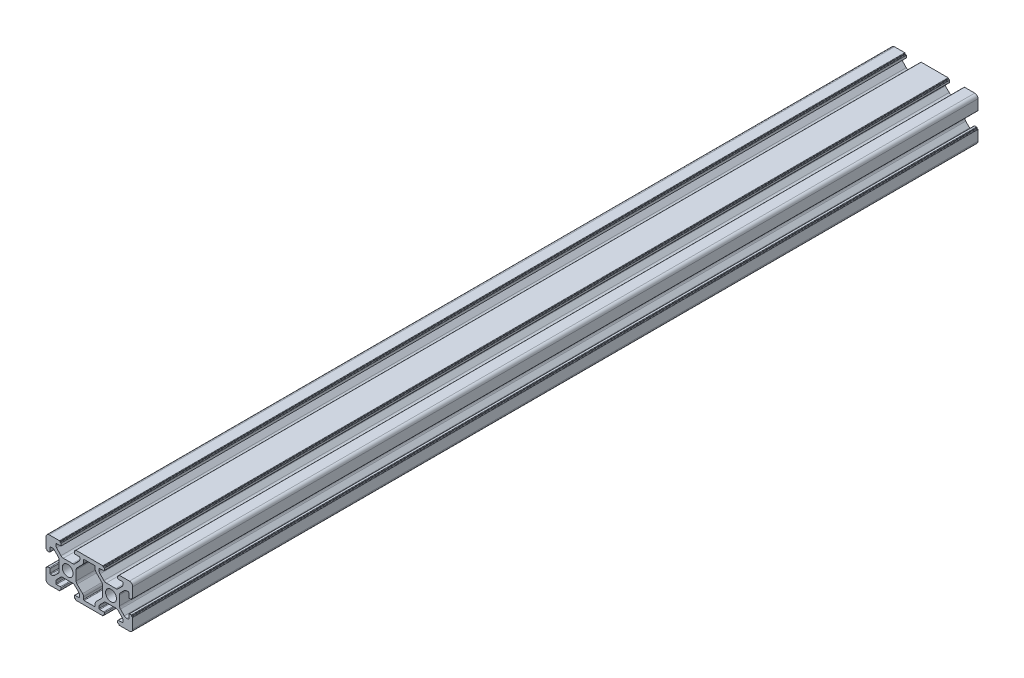
SolidWorks part; units mm, degrees
material "6063-T5"
ref_plane "Front Plane" through (0, 0, 0) normal (0, 0, 1) x (1, 0, 0)
ref_plane "Top Plane" through (0, 0, 0) normal (0, 1, 0) x (1, 0, 0)
ref_plane "Right Plane" through (0, 0, 0) normal (1, 0, 0) x (0, 0, -1)
sketch "Sketch1" plane through (0, 0, 0) normal (0, 0, 1) x (1, 0, 0)
  line L0 (1.5, 0) -> (6.2, 0)
  line L1 (40, 1.5) -> (40, 6.2)
  line L2 (38.5, 20) -> (33.8, 20)
  line L3 (0, 18.5) -> (0, 13.8)
  line L4 (17.6, 1.8) -> (22.4, 1.8)
  line L5 (32.218, 13.9) -> (27.782, 13.9)
  line L6 (26.1, 12.218) -> (26.1, 7.782)
  line L7 (17.6, 18.2) -> (22.4, 18.2)
  line L8 (12.218, 13.9) -> (7.9864, 13.9)
  line L9 (6.1, 12.218) -> (6.1, 7.782)
  line L10 (7.782, 6.1) -> (12.218, 6.1)
  line L11 (13.9, 7.782) -> (13.9, 12.218)
  line L12 (27.782, 6.1) -> (32.218, 6.1)
  line L13 (33.9, 7.782) -> (33.9, 12.218)
  line L14 (26.7213, 14.3393) -> (24.9393, 16.1213)
  line L15 (33.2787, 14.3393) -> (35.0607, 16.1213)
  line L16 (34.3393, 13.2787) -> (36.1213, 15.0607)
  line L17 (25.6607, 6.7213) -> (23.1393, 4.2)
  line L18 (15.2, 1.8) -> (13.4, 1.8)
  line L19 (26.7213, 5.6607) -> (24.9393, 3.8787)
  line L20 (24.8, 1.8) -> (26.6, 1.8)
  line L21 (15.3, 18.2) -> (13.1, 18.2)
  line L22 (13.2787, 14.3393) -> (15.1607, 16.2213)
  line L23 (14.3393, 13.2787) -> (16.8607, 15.8)
  line L24 (5.6607, 6.7213) -> (3.8787, 4.9393)
  line L25 (6.7213, 5.6607) -> (4.9393, 3.8787)
  line L26 (6.897, 14.3689) -> (4.9106, 16.4674)
  line L27 (5.6607, 13.2787) -> (3.8787, 15.0607)
  line L28 (14.3393, 6.7213) -> (16.8607, 4.2)
  line L29 (13.2787, 5.6607) -> (15.0607, 3.8787)
  line L30 (24.8, 18.2) -> (26.6, 18.2)
  line L31 (25.6607, 13.2787) -> (23.1393, 15.8)
  line L32 (34.3393, 6.7213) -> (36.1213, 4.9393)
  line L33 (33.2787, 5.6607) -> (35.0607, 3.8787)
  line L34 (1.8, 15.2) -> (1.8, 13.4)
  line L35 (24.5, 2.1) -> (24.5, 2.818)
  line L36 (4.5, 2.1) -> (4.5, 2.818)
  line L37 (2.818, 4.5) -> (2.1, 4.5)
  line L38 (4.5, 17.9) -> (4.5, 17.4986)
  line L39 (2.818, 15.5) -> (2.1, 15.5)
  line L40 (15.6, 17.9) -> (15.6, 17.282)
  line L41 (15.5, 2.818) -> (15.5, 2.1)
  line L42 (38.2, 15.2) -> (38.2, 13.4)
  line L43 (35.5, 2.818) -> (35.5, 2.1)
  line L44 (37.182, 4.5) -> (37.9, 4.5)
  line L45 (35.5, 17.182) -> (35.5, 17.9)
  line L46 (37.182, 15.5) -> (37.9, 15.5)
  line L47 (17.3, 2.1) -> (17.3, 3.1393)
  line L48 (22.7, 2.1) -> (22.7, 3.1393)
  line L49 (17.3, 17.9) -> (17.3, 16.8607)
  line L50 (22.7, 17.9) -> (22.7, 16.8607)
  line L51 (24.5, 17.9) -> (24.5, 17.182)
  line L52 (6.9, 19.3) -> (6.9, 18.2)
  line L53 (13.1, 19.3) -> (13.1, 18.2)
  line L54 (6.9, 1.5) -> (6.9, 0.7)
  line L55 (13.1, 1.5) -> (13.1, 0.7)
  line L56 (13.8, 0) -> (26.2, 0)
  line L57 (6.6, 1.8) -> (4.8, 1.8)
  line L58 (6.9, 18.2) -> (4.8, 18.2)
  line L59 (6.2, 20) -> (1.5, 20)
  line L60 (39.3, 6.9) -> (38.5, 6.9)
  line L61 (39.3, 13.1) -> (38.5, 13.1)
  line L62 (1.5, 13.1) -> (0.7, 13.1)
  line L63 (1.5, 6.9) -> (0.7, 6.9)
  line L64 (0, 6.2) -> (0, 1.5)
  line L65 (1.8, 6.6) -> (1.8, 4.8)
  line L66 (38.2, 6.6) -> (38.2, 4.8)
  line L67 (40, 13.8) -> (40, 18.5)
  line L68 (33.1, 19.3) -> (33.1, 18.5)
  line L69 (26.9, 19.3) -> (26.9, 18.5)
  line L70 (26.9, 1.5) -> (26.9, 0.7)
  line L71 (33.1, 1.5) -> (33.1, 0.7)
  line L72 (33.8, 0) -> (38.5, 0)
  line L73 (33.4, 1.8) -> (35.2, 1.8)
  line L74 (26.2, 20) -> (13.8, 20)
  line L75 (33.4, 18.2) -> (35.2, 18.2)
  line L76 (6.7, 0.5) -> (6.6, 0.5)
  line L77 (6.4, 0.3) -> (6.4, 0.2)
  line L78 (13.3, 0.5) -> (13.4, 0.5)
  line L79 (13.6, 0.3) -> (13.6, 0.2)
  line L80 (26.7, 0.5) -> (26.6, 0.5)
  line L81 (26.4, 0.3) -> (26.4, 0.2)
  line L82 (33.3, 0.5) -> (33.4, 0.5)
  line L83 (33.6, 0.3) -> (33.6, 0.2)
  line L85 (6.4, 19.8) -> (6.4, 19.7)
  line L86 (6.6, 19.5) -> (6.7, 19.5)
  line L87 (13.6, 19.8) -> (13.6, 19.7)
  line L88 (13.4, 19.5) -> (13.3, 19.5)
  line L89 (26.4, 19.8) -> (26.4, 19.7)
  line L90 (26.6, 19.5) -> (26.7, 19.5)
  line L91 (33.6, 19.8) -> (33.6, 19.7)
  line L92 (33.4, 19.5) -> (33.3, 19.5)
  line L93 (0.5, 13.3) -> (0.5, 13.4)
  line L94 (0.3, 13.6) -> (0.2, 13.6)
  line L95 (0.5, 6.7) -> (0.5, 6.6)
  line L96 (0.3, 6.4) -> (0.2, 6.4)
  line L97 (39.5, 13.3) -> (39.5, 13.4)
  line L98 (39.7, 13.6) -> (39.8, 13.6)
  line L99 (39.5, 6.7) -> (39.5, 6.6)
  line L100 (39.7, 6.4) -> (39.8, 6.4)
  circle A0 centre (10, 10) radius 2.5
  circle A1 centre (30, 10) radius 2.5
  arc A2 (38.5, 0) -> (40, 1.5) centre (38.5, 1.5) ccw
  arc A3 (40, 18.5) -> (38.5, 20) centre (38.5, 18.5) ccw
  arc A4 (1.5, 0) -> (0, 1.5) centre (1.5, 1.5) cw
  arc A5 (1.5, 20) -> (0, 18.5) centre (1.5, 18.5) ccw
  arc A6 (26.7213, 5.6607) -> (27.782, 6.1) centre (27.782, 4.6) cw
  arc A7 (32.218, 6.1) -> (33.2787, 5.6607) centre (32.218, 4.6) cw
  arc A8 (33.9, 7.782) -> (34.3393, 6.7213) centre (35.4, 7.782) ccw
  arc A9 (33.2787, 14.3393) -> (32.218, 13.9) centre (32.218, 15.4) cw
  arc A10 (14.3393, 6.7213) -> (13.9, 7.782) centre (15.4, 7.782) cw
  arc A11 (14.3393, 13.2787) -> (13.9, 12.218) centre (15.4, 12.218) ccw
  arc A12 (25.6607, 6.7213) -> (26.1, 7.782) centre (24.6, 7.782) ccw
  arc A13 (26.1, 12.218) -> (25.6607, 13.2787) centre (24.6, 12.218) ccw
  arc A14 (27.782, 13.9) -> (26.7213, 14.3393) centre (27.782, 15.4) cw
  arc A15 (5.6607, 13.2787) -> (6.1, 12.218) centre (4.6, 12.218) cw
  arc A16 (5.6607, 6.7213) -> (6.1, 7.782) centre (4.6, 7.782) ccw
  arc A17 (13.2787, 5.6607) -> (12.218, 6.1) centre (12.218, 4.6) ccw
  arc A18 (6.7213, 5.6607) -> (7.782, 6.1) centre (7.782, 4.6) cw
  arc A19 (13.2787, 14.3393) -> (12.218, 13.9) centre (12.218, 15.4) cw
  arc A20 (6.897, 14.3689) -> (7.9864, 13.9) centre (7.9864, 15.4) ccw
  arc A21 (36.1213, 4.9393) -> (37.182, 4.5) centre (37.182, 6) ccw
  arc A22 (36.1213, 15.0607) -> (37.182, 15.5) centre (37.182, 14) cw
  arc A23 (35.0607, 16.1213) -> (35.5, 17.182) centre (34, 17.182) ccw
  arc A24 (24.5, 17.182) -> (24.9393, 16.1213) centre (26, 17.182) ccw
  arc A25 (22.7, 16.8607) -> (23.1393, 15.8) centre (24.2, 16.8607) ccw
  arc A26 (17.3, 16.8607) -> (16.8607, 15.8) centre (15.8, 16.8607) cw
  arc A27 (4.9106, 16.4674) -> (4.5, 17.4986) centre (6, 17.4986) cw
  arc A28 (15.6, 17.282) -> (15.1607, 16.2213) centre (14.1, 17.282) cw
  arc A29 (3.8787, 15.0607) -> (2.818, 15.5) centre (2.818, 14) ccw
  arc A30 (3.8787, 4.9393) -> (2.818, 4.5) centre (2.818, 6) cw
  arc A31 (4.9393, 3.8787) -> (4.5, 2.818) centre (6, 2.818) ccw
  arc A32 (35.0607, 3.8787) -> (35.5, 2.818) centre (34, 2.818) cw
  arc A33 (24.9393, 3.8787) -> (24.5, 2.818) centre (26, 2.818) ccw
  arc A34 (22.7, 3.1393) -> (23.1393, 4.2) centre (24.2, 3.1393) cw
  arc A35 (17.3, 3.1393) -> (16.8607, 4.2) centre (15.8, 3.1393) ccw
  arc A36 (15.5, 2.818) -> (15.0607, 3.8787) centre (14, 2.818) ccw
  arc A37 (1.8, 6.6) -> (1.5, 6.9) centre (1.5, 6.6) ccw
  arc A38 (1.8, 13.4) -> (1.5, 13.1) centre (1.5, 13.4) cw
  arc A39 (17.6, 18.2) -> (17.3, 17.9) centre (17.6, 17.9) ccw
  arc A40 (22.4, 1.8) -> (22.7, 2.1) centre (22.4, 2.1) ccw
  arc A41 (17.6, 1.8) -> (17.3, 2.1) centre (17.6, 2.1) cw
  arc A42 (15.2, 1.8) -> (15.5, 2.1) centre (15.2, 2.1) ccw
  arc A43 (6.6, 1.8) -> (6.9, 1.5) centre (6.6, 1.5) cw
  arc A44 (13.4, 1.8) -> (13.1, 1.5) centre (13.4, 1.5) ccw
  arc A45 (24.8, 1.8) -> (24.5, 2.1) centre (24.8, 2.1) cw
  arc A46 (35.2, 1.8) -> (35.5, 2.1) centre (35.2, 2.1) ccw
  arc A47 (26.6, 1.8) -> (26.9, 1.5) centre (26.6, 1.5) cw
  arc A48 (33.4, 1.8) -> (33.1, 1.5) centre (33.4, 1.5) ccw
  arc A49 (26.9, 18.5) -> (26.6, 18.2) centre (26.6, 18.5) cw
  arc A50 (33.1, 18.5) -> (33.4, 18.2) centre (33.4, 18.5) ccw
  arc A51 (37.9, 4.5) -> (38.2, 4.8) centre (37.9, 4.8) ccw
  arc A52 (38.5, 13.1) -> (38.2, 13.4) centre (38.5, 13.4) cw
  arc A53 (38.5, 6.9) -> (38.2, 6.6) centre (38.5, 6.6) ccw
  arc A54 (38.2, 15.2) -> (37.9, 15.5) centre (37.9, 15.2) ccw
  arc A55 (35.2, 18.2) -> (35.5, 17.9) centre (35.2, 17.9) cw
  arc A56 (24.8, 18.2) -> (24.5, 17.9) centre (24.8, 17.9) ccw
  arc A57 (22.4, 18.2) -> (22.7, 17.9) centre (22.4, 17.9) cw
  arc A58 (15.3, 18.2) -> (15.6, 17.9) centre (15.3, 17.9) cw
  arc A59 (4.5, 17.9) -> (4.8, 18.2) centre (4.8, 17.9) cw
  arc A60 (1.8, 15.2) -> (2.1, 15.5) centre (2.1, 15.2) cw
  arc A61 (1.8, 4.8) -> (2.1, 4.5) centre (2.1, 4.8) ccw
  arc A62 (4.5, 2.1) -> (4.8, 1.8) centre (4.8, 2.1) ccw
  arc A63 (34.3393, 13.2787) -> (33.9, 12.218) centre (35.4, 12.218) ccw
  arc A64 (6.4, 0.2) -> (6.2, 0) centre (6.2, 0.2) cw
  arc A65 (6.6, 0.5) -> (6.4, 0.3) centre (6.6, 0.3) ccw
  arc A66 (6.7, 0.5) -> (6.9, 0.7) centre (6.7, 0.7) ccw
  arc A67 (13.6, 0.2) -> (13.8, 0) centre (13.8, 0.2) ccw
  arc A68 (13.4, 0.5) -> (13.6, 0.3) centre (13.4, 0.3) cw
  arc A69 (13.3, 0.5) -> (13.1, 0.7) centre (13.3, 0.7) cw
  arc A70 (26.4, 0.2) -> (26.2, 0) centre (26.2, 0.2) cw
  arc A71 (26.6, 0.5) -> (26.4, 0.3) centre (26.6, 0.3) ccw
  arc A72 (26.7, 0.5) -> (26.9, 0.7) centre (26.7, 0.7) ccw
  arc A73 (33.6, 0.2) -> (33.8, 0) centre (33.8, 0.2) ccw
  arc A74 (33.4, 0.5) -> (33.6, 0.3) centre (33.4, 0.3) cw
  arc A75 (33.3, 0.5) -> (33.1, 0.7) centre (33.3, 0.7) cw
  arc A76 (39.8, 6.4) -> (40, 6.2) centre (39.8, 6.2) cw
  arc A77 (39.5, 6.6) -> (39.7, 6.4) centre (39.7, 6.6) ccw
  arc A78 (39.5, 6.7) -> (39.3, 6.9) centre (39.3, 6.7) ccw
  arc A79 (39.5, 13.3) -> (39.3, 13.1) centre (39.3, 13.3) cw
  arc A80 (39.5, 13.4) -> (39.7, 13.6) centre (39.7, 13.4) cw
  arc A81 (39.8, 13.6) -> (40, 13.8) centre (39.8, 13.8) ccw
  arc A82 (33.3, 19.5) -> (33.1, 19.3) centre (33.3, 19.3) ccw
  arc A83 (33.6, 19.7) -> (33.4, 19.5) centre (33.4, 19.7) cw
  arc A84 (33.6, 19.8) -> (33.8, 20) centre (33.8, 19.8) cw
  arc A85 (26.7, 19.5) -> (26.9, 19.3) centre (26.7, 19.3) cw
  arc A86 (26.4, 19.7) -> (26.6, 19.5) centre (26.6, 19.7) ccw
  arc A87 (26.4, 19.8) -> (26.2, 20) centre (26.2, 19.8) ccw
  arc A88 (0.2, 6.4) -> (0, 6.2) centre (0.2, 6.2) ccw
  arc A89 (0.5, 6.6) -> (0.3, 6.4) centre (0.3, 6.6) cw
  arc A90 (0.5, 6.7) -> (0.7, 6.9) centre (0.7, 6.7) cw
  arc A91 (13.3, 19.5) -> (13.1, 19.3) centre (13.3, 19.3) ccw
  arc A92 (13.6, 19.7) -> (13.4, 19.5) centre (13.4, 19.7) cw
  arc A93 (13.6, 19.8) -> (13.8, 20) centre (13.8, 19.8) cw
  arc A94 (6.2, 20) -> (6.4, 19.8) centre (6.2, 19.8) cw
  arc A95 (6.7, 19.5) -> (6.9, 19.3) centre (6.7, 19.3) cw
  arc A96 (6.4, 19.7) -> (6.6, 19.5) centre (6.6, 19.7) ccw
  arc A97 (0.5, 13.3) -> (0.7, 13.1) centre (0.7, 13.3) ccw
  arc A98 (0.2, 13.6) -> (0, 13.8) centre (0.2, 13.8) cw
  arc A99 (0.5, 13.4) -> (0.3, 13.6) centre (0.3, 13.4) ccw
  point P87 (0, 0)
  point P178 (1.8, 6.9)
  point P181 (1.8, 13.1)
  point P186 (22.7, 1.8)
  point P193 (6.9, 1.8)
  point P204 (33.1, 1.8)
  point P209 (33.1, 18.2)
  point P216 (38.2, 6.9)
  point P243 (6.9, 0.5)
  point P248 (13.6, 0.5)
  point P257 (26.9, 0.5)
extrude "Boss-Extrude2" add sketch "Sketch1" along normal blind 390 contours A57 L7 A39 L49 A26 L23 A11 L11 A10 L28 A35 L47 A41 L4 A40 L48 A34 L17 A12 L6 A13 L31 A25 L50 | A0 | A1 | L59 A5 L3 A98 L94 A99 L93 A97 L62 A38 L34 A60 L39 A29 L27 A15 L9 A16 L24 A30 L37 A61 L65 A37 L63 A90 L95 A89 L96 A88 L64 A4 L0 A64 L77 A65 L76 A66 L54 A43 L57 A62 L36 A31 L25 A18 L10 A17 L29 A36 L41 A42 L18 A44 L55 A69 L78 A68 L79 A67 L56 A70 L81 A71 L80 A72 L70 A47 L20 A45 L35 A33 L19 A6 L12 A7 L33 A32 L43 A46 L73 A48 L71 A75 L82 A74 L83 A73 L72 A2 L1 A76 L100 A77 L99 A78 L60 A53 L66 A51 L44 A21 L32 A8 L13 A63 L16 A22 L46 A54 L42 A52 L61 A79 L97 A80 L98 A81 L67 A3 L2 A84 L91 A83 L92 A82 L68 A50 L75 A55 L45 A23 L15 A9 L5 A14 L14 A24 L51 A56 L30 A49 L69 A85 L90 A86 L89 A87 L74 A93 L87 A92 L88 A91 L53 L21 A58 L40 A28 L22 A19 L8 A20 L26 A27 L38 A59 L58 L52 A95 L86 A96 L85 A94
